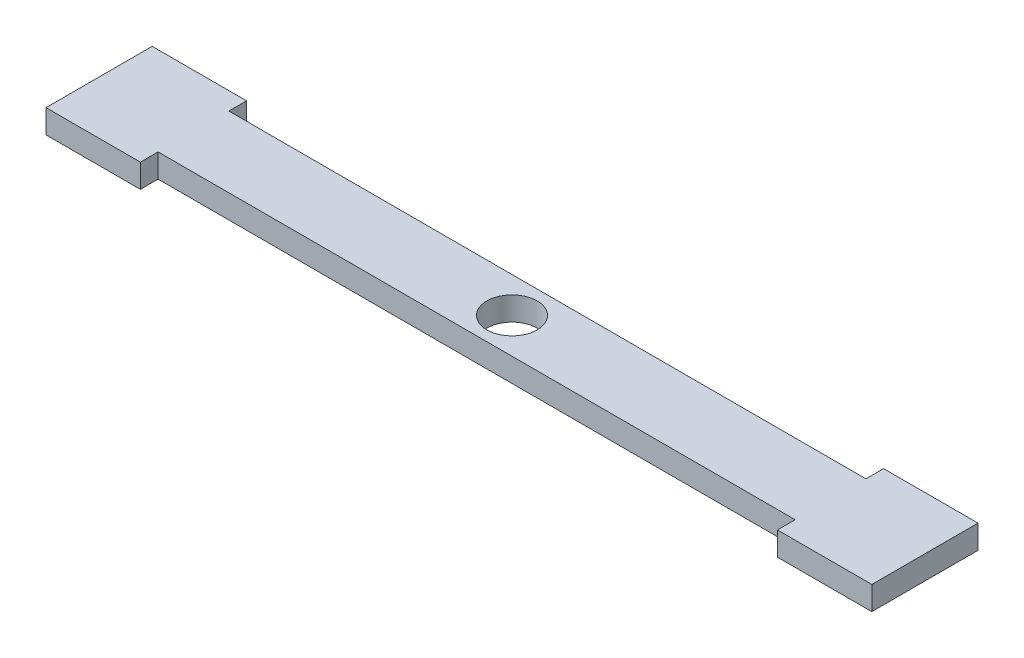
SolidWorks part; units mm, degrees
ref_plane "Front Plane" through (0, 0, 0) normal (0, 0, 1) x (1, 0, 0)
ref_plane "Top Plane" through (0, 0, 0) normal (0, 1, 0) x (1, 0, 0)
ref_plane "Right Plane" through (0, 0, 0) normal (1, 0, 0) x (0, 0, -1)
sketch "Sketch1" plane through (0, 0, 0) normal (0, 1, 0) x (1, 0, 0)
  line L0 (-33.2907, 17.5) -> (236.7093, 17.5)
  line L1 (-33.2907, -12.5) -> (236.7093, -12.5)
  line L7 (-33.2907, -20) -> (-73.2907, -20)
  line L8 (-33.2907, -20) -> (-33.2907, -12.5)
  line L9 (-33.2907, 25) -> (-73.2907, 25)
  line L10 (-73.2907, -20) -> (-73.2907, 25)
  line L11 (-33.2907, -20) -> (-73.2907, 25) construction
  line L12 (-33.2907, 25) -> (-73.2907, -20) construction
  line L13 (276.7093, -20) -> (236.7093, -20)
  line L14 (276.7093, -20) -> (276.7093, 25)
  line L15 (276.7093, 25) -> (236.7093, 25)
  line L16 (236.7093, -20) -> (236.7093, -12.5)
  line L17 (276.7093, -20) -> (236.7093, 25) construction
  line L18 (276.7093, 25) -> (236.7093, -20) construction
  line L19 (-33.2907, 17.5) -> (-33.2907, 25)
  line L20 (236.7093, 17.5) -> (236.7093, 25)
  line L21 (-73.2907, 2.5) -> (276.7093, 2.5) construction
  circle A0 centre (101.7093, 2.5) radius 10.65
  point P0 (0, 0)
  point P6 (-53.2907, 2.5)
  point P11 (256.7093, 2.5)
  dimension "D3" = 21.3
  dimension "D1" = 45
  dimension "D2" = 30
  dimension "D4" = 45
  dimension "D5" = 350
  dimension "D6" = 40
  dimension "D7" = 40
  dimension "D8" = 270
extrude "Boss-Extrude1" add sketch "Sketch1" along normal blind 10
